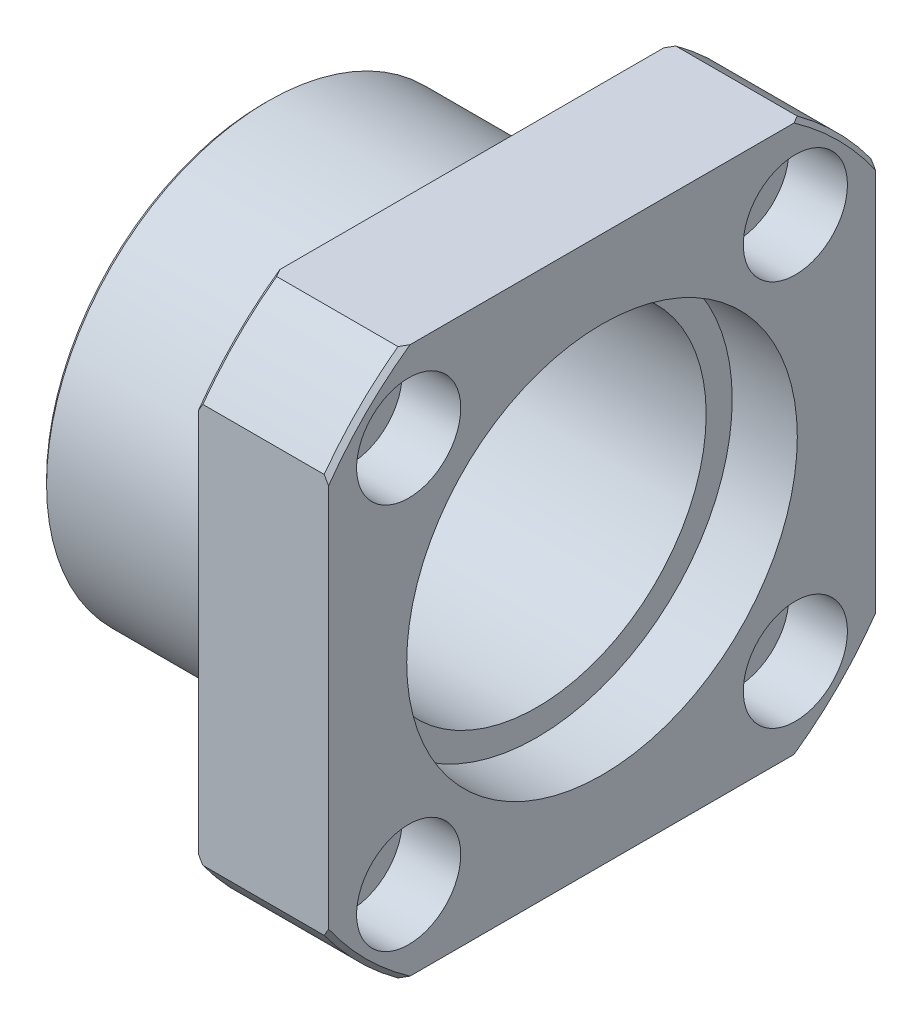
SolidWorks part; units mm, degrees
ref_plane "Front Plane" through (0, 0, 0) normal (0, 0, 1) x (1, 0, 0)
ref_plane "Top Plane" through (0, 0, 0) normal (0, 1, 0) x (1, 0, 0)
ref_plane "Right Plane" through (0, 0, 0) normal (1, 0, 0) x (0, 0, -1)
ref_plane "Plane1" through (26, 0, 0) normal (1, 0, 0) x (0, 0, -1)
sketch "Sketch1" plane through (26, 0, 0) normal (1, 0, 0) x (0, 0, -1)
  line L0 (21, -15.3297) -> (21, 15.3297)
  line L1 (15.3297, 21) -> (-15.3297, 21)
  line L2 (-21, 15.3297) -> (-21, -15.3297)
  line L3 (-15.3297, -21) -> (15.3297, -21)
  arc A0 (21, 15.3297) -> (15.3297, 21) centre (0, 0) ccw
  arc A1 (-15.3297, 21) -> (-21, 15.3297) centre (0, 0) ccw
  arc A2 (-21, -15.3297) -> (-15.3297, -21) centre (0, 0) ccw
  arc A3 (15.3297, -21) -> (21, -15.3297) centre (0, 0) ccw
extrude "Boss-Extrude1" add sketch "Sketch1" against normal blind 10
sketch "Sketch2" plane through (0, 0, 0) normal (0, 0, 1) x (1, 0, 0)
  line L0 (0, 17) -> (0, 0)
  line L1 (0, 0) -> (16, 0)
  line L2 (16, 0) -> (16, 17)
  line L3 (16, 17) -> (0, 17)
  line L4 (0, 0) -> (16, 0) construction
revolve "Revolve1" add sketch "Sketch2" angle 360 about L4
sketch "Sketch3" plane through (0, 0, 0) normal (0, 0, 1) x (1, 0, 0)
  line L0 (0, 7.25) -> (0, 0)
  line L1 (0, 0) -> (26, 0)
  line L2 (26, 0) -> (26, 15)
  line L3 (26, 15) -> (21, 15)
  line L4 (21, 15) -> (21, 13)
  line L5 (21, 13) -> (5, 13)
  line L6 (5, 13) -> (5, 7.25)
  line L7 (5, 7.25) -> (0, 7.25)
  line L8 (0, 0) -> (26, 0) construction
revolve "Cut-Revolve1" cut sketch "Sketch3" angle 360 about L8
hole_wizard "CBORE for M4 Hex Head Machine Screw1" positions "Sketch5" profile "Sketch4" counterbore size "M4" standard "ANSI Metric"
sketch "Sketch5" plane through (26, 0, 0) normal (1, 0, 0) x (0, 0, -1)
  point P0 (-14.8492, 14.8492)
  point P1 (14.8492, -14.8492)
  point P2 (14.8492, 14.8492)
  point P3 (-14.8492, -14.8492)
sketch "Sketch4" plane through (26, 14.8492, 14.8492) normal (0, 1, 0) x (0, 0, -1)
  line L0 (0, 0) -> (0, 26)
  line L1 (0, 26) -> (2.25, 26)
  line L3 (2.25, 26) -> (2.25, 4.5)
  line L4 (2.25, 4.5) -> (4, 4.5)
  line L5 (4, 4.5) -> (4, 0)
  line L7 (4, 0) -> (0, 0)
  line L11 (0, -6.35) -> (0, 107.95) construction
  dimension "Thru Hole Dia." = 4.5
  dimension "Thru Hole Depth" = 26
  dimension "C'Bore Dia." = 8
  dimension "C'Bore Depth" = 4.5
chamfer "Chamfer1" distance 0.34 angle 45 9 edges at (16, -18.3848, -18.3848) (16, 18.3848, 18.3848) (26, 18.3848, -18.3848) (16, -18.3848, 18.3848) (26, -18.3848, 18.3848) (0, 0, -17) (26, 18.3848, 18.3848) (26, -18.3848, -18.3848) (16, 18.3848, -18.3848)
fillet "Fillet1" radius 0.3 1 edges at (16, 0, -17)
